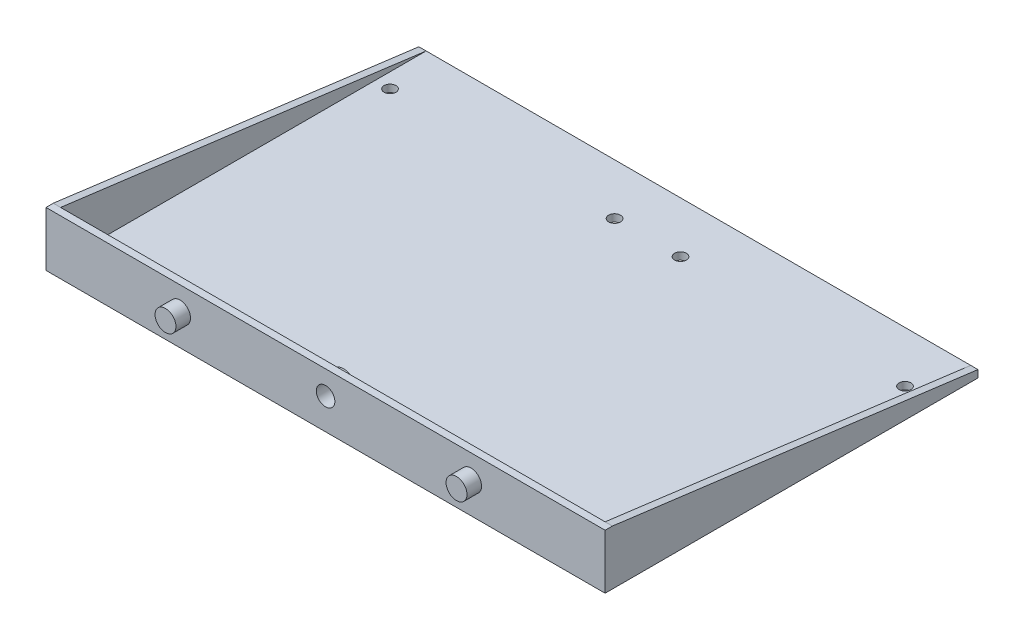
SolidWorks part; units mm, degrees
ref_plane "Front Plane" through (0, 0, 0) normal (0, 0, 1) x (1, 0, 0)
ref_plane "Top Plane" through (0, 0, 0) normal (0, 1, 0) x (1, 0, 0)
ref_plane "Right Plane" through (0, 0, 0) normal (1, 0, 0) x (0, 0, -1)
sketch "Sketch1" plane through (0, 0, 0) normal (0, 1, 0) x (1, 0, 0)
  line L0 (69.85, 0) -> (79.85, 0)
  line L1 (0, 0) -> (69.85, 0)
  line L2 (0, 0) -> (0, 100.5)
  line L3 (0, 100.5) -> (69.85, 100.5)
  line L4 (69.85, 0) -> (69.85, 100.5)
  line L5 (69.85, 100.5) -> (79.85, 100.5)
  line L6 (79.85, 0) -> (149.7, 0)
  line L7 (79.85, 0) -> (79.85, 100.5)
  line L8 (79.85, 100.5) -> (149.7, 100.5)
  line L9 (149.7, 0) -> (149.7, 100.5)
  line L10 (0, 100.5) -> (0, 86.5)
  line L11 (0, 86.5) -> (4.07, 86.5)
  line L12 (4.07, 86.5) -> (65.79, 86.5)
  line L13 (65.79, 86.5) -> (65.79, 9.9)
  line L14 (65.79, 9.9) -> (4.07, 9.9)
  circle A0 centre (4.07, 86.5) radius 1.625
  circle A1 centre (4.07, 9.9) radius 1.625
  circle A2 centre (65.79, 9.9) radius 1.625
  circle A3 centre (65.79, 86.5) radius 1.625
  circle A4 centre (145.64, 9.9) radius 1.625
  circle A5 centre (83.92, 9.9) radius 1.625
  circle A6 centre (83.92, 86.5) radius 1.625
  circle A7 centre (145.64, 86.5) radius 1.625
extrude "Boss-Extrude1" add sketch "Sketch1" along normal blind 2
ref_plane "Plane1" through (149.7, 0, 0) normal (1, 0, 0) x (0, 0, -1)
sketch "Sketch3" plane through (0, 0, 0) normal (0, 0, 1) x (1, 0, 0)
  line L0 (0, 2) -> (149.7, 2)
  line L1 (149.7, -41.1675) -> (149.7, 41.1675) construction
  line L2 (0, 2) -> (149.7, 2) construction
  line L3 (149.7, 2) -> (159.7, 2)
  line L4 (159.7, 2) -> (159.7, -13)
  line L5 (0, 2) -> (-10, 2)
  line L6 (-10, 2) -> (-10, -13)
  line L8 (-10, 2) -> (159.7, 2)
  line L9 (-10, 2) -> (-10, -13)
  line L10 (-10, -13) -> (159.7, -13)
  line L11 (159.7, 2) -> (159.7, -13)
  line M5 (0, 0) -> (149.7, 0)
  line M6 (149.7, 0) -> (149.7, 2)
  line M7 (149.7, 2) -> (0, 2)
  line M8 (0, 2) -> (0, 0)
extrude "Boss-Extrude2" add sketch "Sketch3" along normal blind 2 contours L6 L10 L4 L3 L5 M6 M5 M8 | M8 M5 M6 M7
sketch "Sketch4" plane through (0, 0, 0) normal (-1, 0, 0) x (0, 0, 1)
  line L0 (-100.5, 0) -> (0, -13)
  line L1 (0, -13) -> (0, 2)
  line L2 (0, 2) -> (-100.5, 2)
  line L7 (-100.5, 0) -> (0, 0)
  line L8 (0, 0) -> (0, 2)
  line L9 (0, 2) -> (-100.5, 2)
  line L10 (-100.5, 2) -> (-100.5, 0)
  line L11 (-100.5, 0) -> (0, 0)
  line L12 (0, 0) -> (0, 2)
  line L13 (0, 2) -> (-100.5, 2)
  line M1 (-100.5, 0) -> (0, 0)
  line M2 (0, 0) -> (0, 2)
  line M3 (0, 2) -> (-100.5, 2)
  line M4 (-100.5, 2) -> (-100.5, 0)
  dimension "D1" = 0
extrude "Boss-Extrude3" add sketch "Sketch4" along normal blind 2 contours L0 L1 M1 | M4 M1 M2 M3 | L2 L13
sketch "Sketch5" plane through (149.7, 0, 0) normal (1, 0, 0) x (0, 0, -1)
  line L0 (100.5, 0) -> (0, -13)
  line L1 (0, -13) -> (0, 2)
  line L2 (0, 2) -> (100.5, 2)
  line L3 (100.5, 2) -> (100.5, 0)
extrude "Boss-Extrude4" add sketch "Sketch5" along normal blind 2
sketch "Sketch6" plane through (0, 0, 0) normal (0, 0, -1) x (-1, 0, 0)
  line L0 (10, 2) -> (2, 2) construction
  line L1 (2, 2) -> (2, -13) construction
  line L2 (2, -13) -> (10, -13) construction
  line L3 (10, -13) -> (10, 2) construction
  line L4 (-159.7, -13) -> (-151.7, -13) construction
  line L5 (-151.7, -13) -> (-151.7, 2) construction
  line L6 (-151.7, 2) -> (-159.7, 2) construction
  line L7 (-159.7, 2) -> (-159.7, -13) construction
  line L8 (10, 2) -> (2, 2)
  line L9 (2, 2) -> (2, -13)
  line L10 (2, -13) -> (10, -13)
  line L11 (10, -13) -> (10, 2)
  line L12 (-159.7, -13) -> (-151.7, -13)
  line L13 (-151.7, -13) -> (-151.7, 2)
  line L14 (-151.7, 2) -> (-159.7, 2)
  line L15 (-159.7, 2) -> (-159.7, -13)
extrude "Boss-Extrude5" add sketch "Sketch6" along normal blind 3
sketch "Sketch8" plane through (0, 0, -3) normal (0, 0, -1) x (-1, 0, 0)
  line L0 (-159.7, 2) -> (-159.7, -13)
  line L1 (-159.7, -5.5) -> (-151.7, -5.5)
  line L2 (-151.7, -12.6119) -> (-151.7, 2) construction
  line L3 (10, -5.5) -> (2, -5.5)
  line L4 (10, -13) -> (10, 2) construction
  line L5 (2, 2) -> (2, -12.6119) construction
  circle A0 centre (-155.7, -5.5) radius 2.55
  circle A1 centre (6, -5.5) radius 2.55
extrude "Cut-Extrude1" cut sketch "Sketch8" against normal blind 10 contours L1 A0 | L1 A0 | L3 A1 | L3 A1
fillet "Fillet1" radius 3 4 edges at (159.7, -13, -0.5) (159.7, 2, -0.5) (-10, -13, -0.5) (-10, 2, -0.5)
sketch "Sketch9" plane through (0, 0, 0) normal (0, 0, -1) x (-1, 0, 0)
  line L0 (-74.85, 0) -> (-74.85, -13)
  line L1 (0, 0) -> (-149.7, 0) construction
  line L2 (0, -13) -> (-149.7, -13) construction
  circle A0 centre (-74.85, -6.5) radius 2.55
extrude "Cut-Extrude2" cut sketch "Sketch9" against normal blind 10 contours L0 A0 | L0 A0
sketch "Sketch10" plane through (0, 0, 0) normal (0, 0, -1) x (-1, 0, 0)
  circle A0 centre (-74.85, -6.5) radius 4
  circle A1 centre (-74.85, -6.5) radius 2.55
extrude "Boss-Extrude6" add sketch "Sketch10" along normal blind 3
sketch "Sketch12" plane through (0, 0, 2) normal (0, 0, 1) x (1, 0, 0)
  line L0 (74.85, -6.5) -> (34.85, -6.5)
  line L1 (34.85, -6.5) -> (114.85, -6.5)
  circle A0 centre (34.85, -6.5) radius 2.875
  circle A1 centre (114.85, -6.5) radius 2.875
extrude "Boss-Extrude7" add sketch "Sketch12" along normal blind 4
sketch "Sketch13" plane through (0, 0, -3) normal (0, 0, -1) x (-1, 0, 0)
  line L1 (-151.7, 2) -> (-162.6469, 2)
  line L2 (-151.7, 2) -> (-151.7, -15.5804)
  line L3 (-151.7, -15.5804) -> (-162.6469, -15.5804)
  line L4 (-162.6469, 2) -> (-162.6469, -15.5804)
  line L5 (2, 2) -> (12.2965, 2)
  line L6 (2, 2) -> (2, -21.4335)
  line L7 (2, -21.4335) -> (12.2965, -21.4335)
  line L8 (12.2965, 2) -> (12.2965, -21.4335)
extrude "Cut-Extrude3" cut sketch "Sketch13" against normal blind 43
ref_plane "Plane2" through (0, 7, 0) normal (0, 1, 0) x (1, 0, 0)
mirror "Mirror6" about plane through (0, 7, 0) normal (0, 1, 0) of bodies 111
sketch "Sketch15" plane through (0, 0, 0) normal (0, 0, -1) x (-1, 0, 0)
  line L1 (-171.6238, 8.299) -> (21.9238, 8.299)
  line L2 (-171.6238, 8.299) -> (-171.6238, -28.3971)
  line L3 (-171.6238, -28.3971) -> (21.9238, -28.3971)
  line L4 (21.9238, 8.299) -> (21.9238, -28.3971)
extrude "Cut-Extrude4" cut sketch "Sketch15" against normal blind 25 and the other way blind 132
